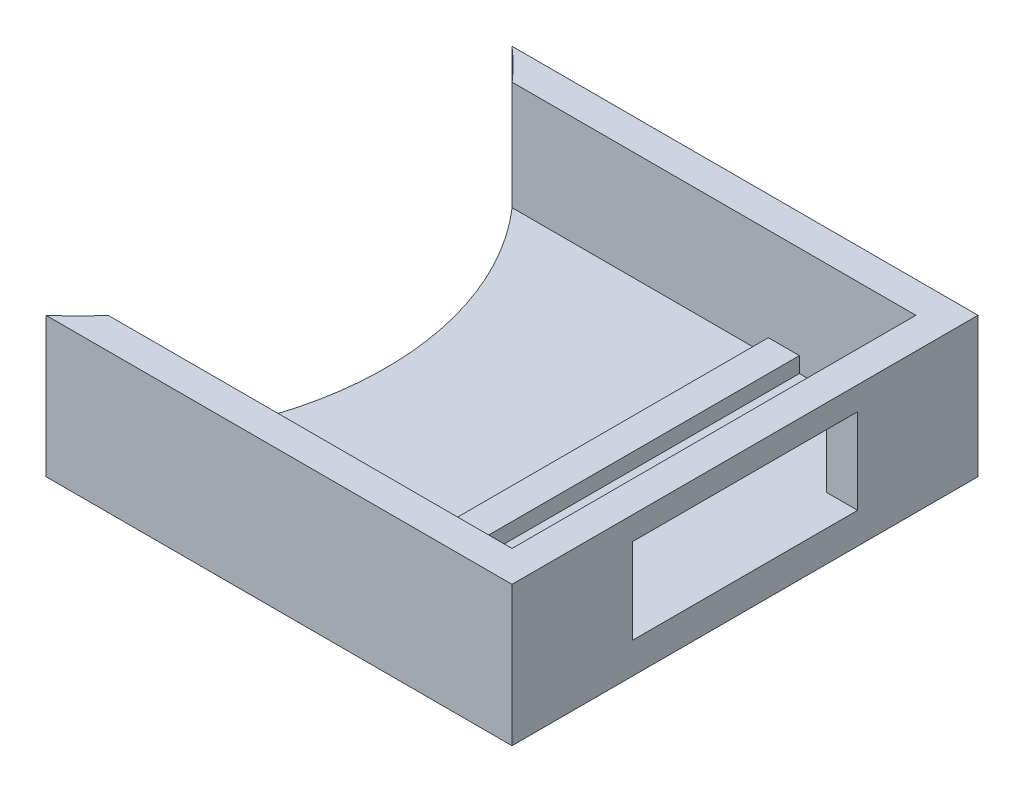
SolidWorks part; units mm, degrees
ref_plane "前视基准面" through (0, 0, 0) normal (0, 0, 1) x (1, 0, 0)
ref_plane "上视基准面" through (0, 0, 0) normal (0, 1, 0) x (1, 0, 0)
ref_plane "右视基准面" through (0, 0, 0) normal (1, 0, 0) x (0, 0, -1)
sketch "草图1" plane through (0, 0, 0) normal (0, 1, 0) x (1, 0, 0)
  line L0 (-15.9216, 18.9467) -> (-15.9216, -11.0533)
  line L1 (-15.9216, 18.9467) -> (14.0784, 18.9467)
  line L2 (14.0784, 18.9467) -> (14.0784, -11.0533)
  line L3 (14.0784, -11.0533) -> (-15.9216, -11.0533)
  circle A0 centre (-28.846, 3.9467) radius 19.8
  dimension "D1" = 39.6
  dimension "D2" = 30
  dimension "D3" = 30
extrude "凸台-拉伸1" add sketch "草图1" along normal blind 2 contours A0 L3 L2 L1
sketch "草图2" plane through (0, 2, 0) normal (0, 1, 0) x (1, 0, 0)
  line L0 (-15.9216, 18.9467) -> (14.0784, 18.9467)
  line L1 (14.0784, 18.9467) -> (14.0784, -11.0533)
  line L2 (14.0784, -11.0533) -> (-15.9216, -11.0533)
  line L3 (-13.9115, 16.9467) -> (12.0784, 16.9467)
  line L4 (12.0784, 16.9467) -> (12.0784, -9.0533)
  line L5 (12.0784, -9.0533) -> (-13.9115, -9.0533)
  arc A0 (-15.9216, 18.9467) -> (-9.046, 3.9467) centre (-28.846, 3.9467) ccw
  arc A1 (-15.9216, -11.0533) -> (-15.9216, 18.9467) centre (-28.846, 3.9467) ccw construction
  arc M7 (-15.9216, 18.9467) -> (-15.9216, -11.0533) centre (-28.846, 3.9467) cw
  line M8 (-15.9216, -11.0533) -> (14.0784, -11.0533)
  line M9 (14.0784, -11.0533) -> (14.0784, 18.9467)
  line M10 (14.0784, 18.9467) -> (-15.9216, 18.9467)
  dimension "D1" = 2
  dimension "D2" = 2
  dimension "D3" = 2
extrude "凸台-拉伸2" add sketch "草图2" along normal blind 7 contours L4 L5 L3 M7 M8 M9 M10
sketch "草图3" plane through (12.0784, 0, 0) normal (-1, 0, 0) x (0, 0, 1)
  line L0 (-16.9467, 2) -> (9.0533, 2) construction
  line L1 (-11.1967, 2) -> (3.3033, 2)
  line L2 (-11.1967, 2) -> (-11.1967, 7.5)
  line L3 (-11.1967, 7.5) -> (3.3033, 7.5)
  line L4 (3.3033, 2) -> (3.3033, 7.5)
  line L5 (-16.9467, 9) -> (9.0533, 9) construction
  point P8 (-3.9467, 9)
  point P9 (-3.9467, 7.5)
  dimension "D1" = 5.5
  dimension "D2" = 14.5
  dimension "D3" = 0
extrude "切除-拉伸1" cut sketch "草图3" against normal blind 2
sketch "草图4" plane through (0, 2, 0) normal (0, 1, 0) x (1, 0, 0)
  line L0 (-13.9115, 16.9467) -> (12.0784, 16.9467) construction
  line L1 (2.5784, 16.9467) -> (4.5784, 16.9467)
  line L2 (2.5784, 16.9467) -> (2.5784, -9.0533)
  line L3 (2.5784, -9.0533) -> (4.5784, -9.0533)
  line L4 (4.5784, 16.9467) -> (4.5784, -9.0533)
  line L5 (12.0784, -9.0533) -> (-13.9115, -9.0533) construction
  line L6 (12.0784, 16.9467) -> (12.0784, -9.0533) construction
  dimension "D1" = 2
  dimension "D2" = 7.5
extrude "凸台-拉伸3" add sketch "草图4" along normal blind 1
